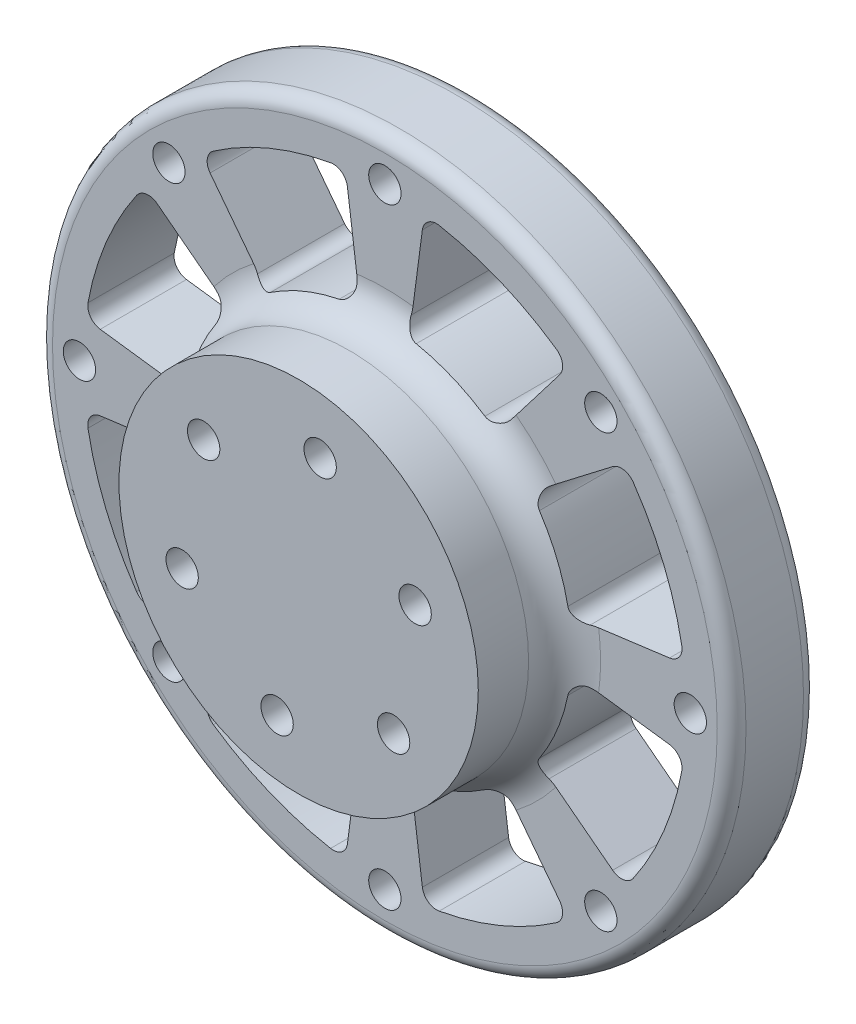
SolidWorks part; units mm, degrees
ref_plane "前视基准面" through (0, 0, 0) normal (0, 0, 1) x (1, 0, 0)
ref_plane "上视基准面" through (0, 0, 0) normal (0, 1, 0) x (1, 0, 0)
ref_plane "右视基准面" through (0, 0, 0) normal (1, 0, 0) x (0, 0, -1)
other "Configuration Table"
sketch "草图6" plane through (0, 0, 0) normal (0, 0, 1) x (1, 0, 0)
  circle A0 centre (0, 0) radius 48.25
  circle A1 centre (0, 0) radius 42.5
  circle A2 centre (0, 42.5) radius 2.25
  circle A3 centre (30.052, 30.052) radius 2.25
  circle A4 centre (42.5, 0) radius 2.25
  circle A5 centre (30.052, -30.052) radius 2.25
  circle A6 centre (0, -42.5) radius 2.25
  circle A7 centre (-30.052, -30.052) radius 2.25
  circle A8 centre (-42.5, 0) radius 2.25
  circle A9 centre (-30.052, 30.052) radius 2.25
  point P5 (0, 0)
  point P24 (0, 0)
  dimension "D1" = 96.5
  dimension "D2" = 85
  dimension "D3" = 4.5
  dimension "D4" = 8
extrude "凸台-拉伸4" add sketch "草图6" along normal blind 12 contours A9 A1 A8 A7 A6 A5 A4 A3 A2 | A0 A9 A1 A2 A3 A4 A5 A6 A7 A8
sketch "草图7" plane through (0, 0, 12) normal (0, 0, 1) x (1, 0, 0)
  line L0 (0, 17.25) -> (0, -17.25)
  line L2 (2.9954, 16.9879) -> (-2.9954, -16.9879) construction
  circle A0 centre (0, 0) radius 25
  circle A1 centre (0, 0) radius 17.25 construction
  circle A2 centre (2.9954, 16.9879) radius 2.25
  circle A3 centre (16.2097, 5.8998) radius 2.25
  circle A4 centre (13.2143, -11.0881) radius 2.25
  circle A5 centre (-2.9954, -16.9879) radius 2.25
  circle A6 centre (-16.2097, -5.8998) radius 2.25
  circle A7 centre (-13.2143, 11.0881) radius 2.25
  point P11 (0, 0)
  point P24 (0, 0)
  dimension "D1" = 50
  dimension "D2" = 34.5
  dimension "D3" = 10
  dimension "D4" = 4.5
  dimension "D5" = 6
extrude "凸台-拉伸5" add sketch "草图7" along normal blind 12
sketch "草图8" plane through (0, 0, 24) normal (0, 0, 1) x (1, 0, 0)
  circle A0 centre (-13.2143, 11.0881) radius 2.25 construction
  circle A1 centre (0, 0) radius 25
  circle A2 centre (0, 0) radius 25
  circle A3 centre (-13.2143, 11.0881) radius 2.25
  circle A4 centre (2.9954, 16.9879) radius 2.25 construction
  circle A5 centre (16.2097, 5.8998) radius 2.25 construction
  circle A6 centre (13.2143, -11.0881) radius 2.25 construction
  circle A7 centre (-2.9954, -16.9879) radius 2.25 construction
  circle A8 centre (-16.2097, -5.8998) radius 2.25 construction
  circle A9 centre (2.9954, 16.9879) radius 2.25
  circle A10 centre (16.2097, 5.8998) radius 2.25
  circle A11 centre (13.2143, -11.0881) radius 2.25
  circle A12 centre (-2.9954, -16.9879) radius 2.25
  circle A13 centre (-16.2097, -5.8998) radius 2.25
  point P21 (0, 0)
  dimension "D1" = 0
extrude "切除-拉伸6" cut sketch "草图8" against normal blind 35 contours A13 | A12 | A11 | A10 | A9 | A3
fillet "圆角1" radius 5 1 edges at (25, 0, 12)
sketch "草图9" plane through (0, 0, 0) normal (0, 0, -1) x (-1, 0, 0)
  line L0 (0, 0) -> (-5.4821, 41.6407)
  line L1 (0, 0) -> (-25.568, 33.3208)
  line L2 (0, 42) -> (0, 0) construction
  line L3 (0, 0) -> (5.4821, 41.6407)
  line L4 (0, 0) -> (25.568, 33.3208)
  line L5 (0, 0) -> (33.3208, 25.568)
  line L6 (0, 0) -> (41.6407, 5.4821)
  line L7 (0, 0) -> (41.6407, -5.4821)
  line L8 (0, 0) -> (33.3208, -25.568)
  line L9 (0, 0) -> (25.568, -33.3208)
  line L10 (0, 0) -> (5.4821, -41.6407)
  line L11 (0, 0) -> (-5.4821, -41.6407)
  line L12 (0, 0) -> (-25.568, -33.3208)
  line L13 (0, 0) -> (-33.3208, -25.568)
  line L14 (0, 0) -> (-41.6407, -5.4821)
  line L15 (0, 0) -> (-41.6407, 5.4821)
  line L16 (0, 0) -> (-33.3208, 25.568)
  circle A0 centre (0, 0) radius 42
  circle A1 centre (0, 0) radius 27
  point P23 (0, 0)
  dimension "D1" = 84
  dimension "D2" = 54
  dimension "D3" = 30
  dimension "D4" = 7.5
  dimension "D5" = 8
extrude "切除-拉伸7" cut sketch "草图9" against normal blind 35 contours A1 L0 A0 L1 | A1 L4 A0 L3 | A1 L6 A0 L5 | A1 L8 A0 L7 | A1 L10 A0 L9 | A1 L12 A0 L11 | A1 L14 A0 L13 | A1 L16 A0 L15
fillet "圆角2" radius 2 34 edges at (48.25, 0, 12) (48.25, 0, 0) (41.6407, -5.4821, 6) (26.769, -3.5242, 6.5) (21.4205, -16.4366, 6.5) (33.3208, -25.568, 6) (33.3208, 25.568, 6) (21.4205, 16.4366, 6.5) (41.6407, 5.4821, 6) (26.769, 3.5242, 6.5) (25.568, 33.3208, 6) (16.4366, 21.4205, 6.5) (3.5242, 26.769, 6.5) (5.4821, 41.6407, 6) (-25.568, 33.3208, 6) (-5.4821, 41.6407, 6) (-3.5242, 26.769, 6.5) (-16.4366, 21.4205, 6.5) (-21.4205, 16.4366, 6.5) (-26.769, 3.5242, 6.5) (-33.3208, 25.568, 6) (-41.6407, 5.4821, 6) (-33.3208, -25.568, 6) (-41.6407, -5.4821, 6) (-26.769, -3.5242, 6.5) (-21.4205, -16.4366, 6.5) (-5.4821, -41.6407, 6) (-25.568, -33.3208, 6) (-16.4366, -21.4205, 6.5) (-3.5242, -26.769, 6.5) (5.4821, -41.6407, 6) (25.568, -33.3208, 6) (16.4366, -21.4205, 6.5) (3.5242, -26.769, 6.5)
